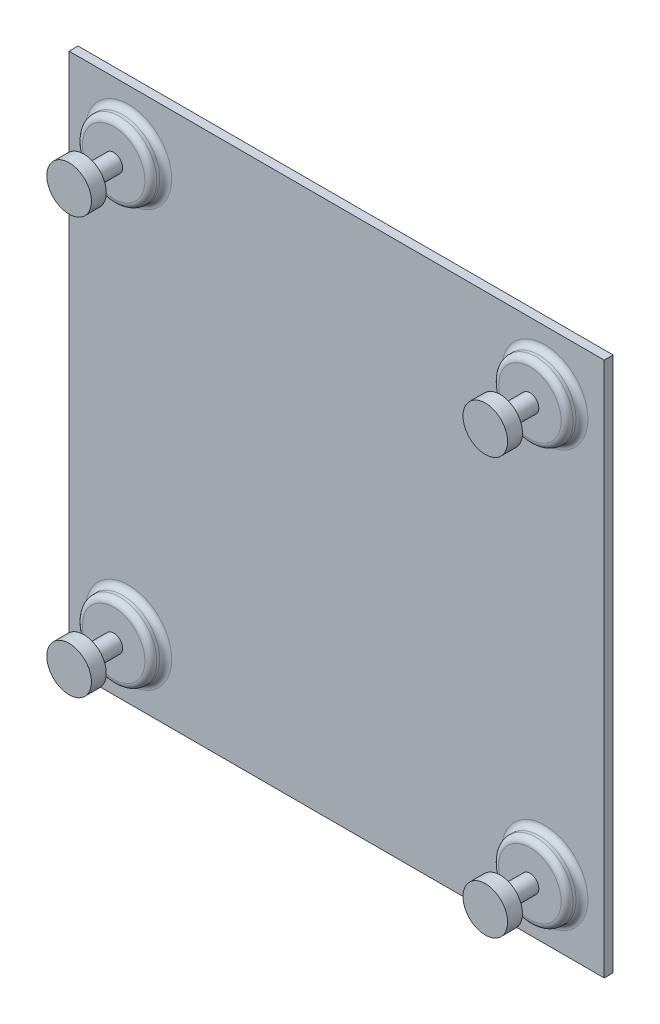
SolidWorks part; units mm, degrees
ref_plane "Front Plane" through (0, 0, 0) normal (0, 0, 1) x (1, 0, 0)
ref_plane "Top Plane" through (0, 0, 0) normal (0, 1, 0) x (1, 0, 0)
ref_plane "Right Plane" through (0, 0, 0) normal (1, 0, 0) x (0, 0, -1)
sketch "Sketch1" plane through (0, 0, 0) normal (0, 0, 1) x (1, 0, 0)
  line L1 (-114.3, -114.3) -> (114.3, -114.3)
  line L2 (-114.3, -114.3) -> (-114.3, 114.3)
  line L3 (-114.3, 114.3) -> (114.3, 114.3)
  line L4 (114.3, -114.3) -> (114.3, 114.3)
  line L5 (-114.3, -114.3) -> (114.3, 114.3) construction
  line L6 (-114.3, 114.3) -> (114.3, -114.3) construction
  point P0 (0, 0)
  dimension "D1" = 228.6
  dimension "D2" = 228.6
extrude "Boss-Extrude1" add sketch "Sketch1" along normal blind 3.81
sketch "Sketch2" plane through (0, 0, 3.81) normal (0, 0, 1) x (1, 0, 0)
  line L0 (114.3, -114.3) -> (114.3, 114.3) construction
  line L1 (-114.3, -114.3) -> (114.3, -114.3) construction
  line L2 (0, 0) -> (24.727, 0) construction
  line L3 (24.727, 0) -> (0, 0) construction
  line L4 (0, 0) -> (0, 26.0531) construction
  circle A0 centre (88.9, -88.9) radius 15.875
  circle A1 centre (88.9, 88.9) radius 15.875
  circle A2 centre (-88.9, -88.9) radius 15.875
  circle A3 centre (-88.9, 88.9) radius 15.875
  dimension "D1" = 31.75
  dimension "D2" = 25.4
  dimension "D3" = 25.4
extrude "Boss-Extrude2" add sketch "Sketch2" along normal blind 6.35
sketch "Sketch3" plane through (0, 0, 10.16) normal (0, 0, 1) x (1, 0, 0)
  circle A0 centre (-88.9, -88.9) radius 3.81
  circle A1 centre (-88.9, 88.9) radius 3.81
  circle A2 centre (88.9, -88.9) radius 3.81
  circle A3 centre (88.9, 88.9) radius 3.81
  dimension "D1" = 7.62
  dimension "D2" = 7.62
  dimension "D3" = 7.62
  dimension "D4" = 7.62
extrude "Boss-Extrude3" add sketch "Sketch3" along normal blind 12.7
sketch "Sketch4" plane through (0, 0, 22.86) normal (0, 0, 1) x (1, 0, 0)
  circle A0 centre (-88.9, -88.9) radius 9.525
  circle A1 centre (-88.9, 88.9) radius 9.525
  circle A2 centre (88.9, 88.9) radius 9.525
  circle A3 centre (88.9, -88.9) radius 9.525
  dimension "D1" = 19.05
  dimension "D2" = 19.05
  dimension "D3" = 19.05
  dimension "D4" = 19.05
extrude "Boss-Extrude4" add sketch "Sketch4" along normal blind 6.35
fillet "Fillet1" radius 2.54 4 edges at (104.775, -88.9, 10.16) (73.025, 88.9, 10.16) (-73.025, 88.9, 10.16) (-104.775, -88.9, 10.16)
fillet "Fillet2" radius 2.54 4 edges at (73.025, -88.9, 3.81) (73.025, 88.9, 3.81) (-104.775, 88.9, 3.81) (-104.775, -88.9, 3.81)
sketch "Sketch5" plane through (0, 0, 0) normal (0, 0, -1) x (-1, 0, 0)
  point P0 (0, 0)
